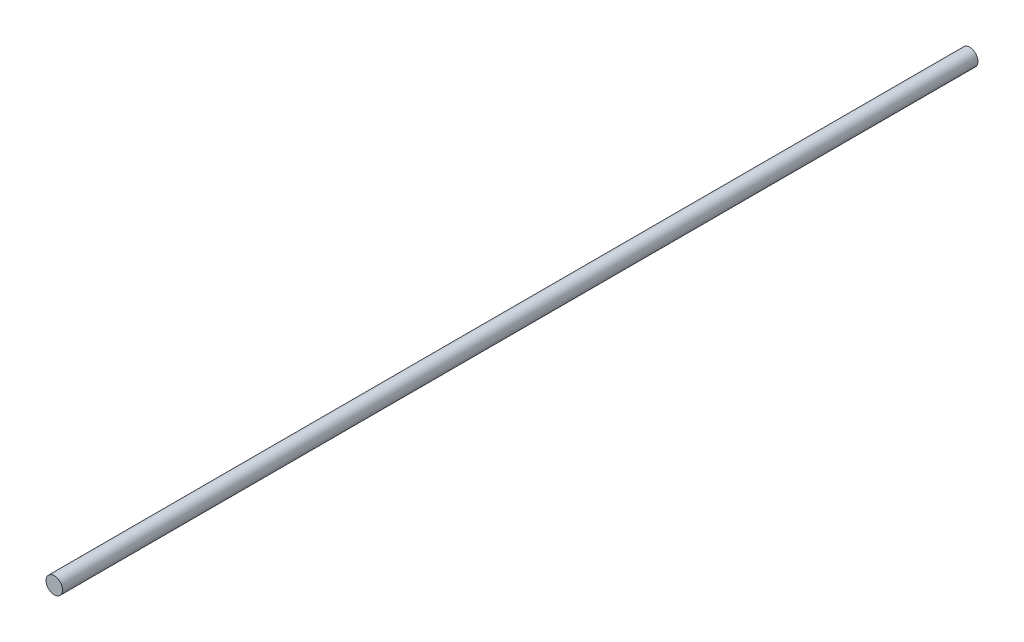
SolidWorks part; units mm, degrees
ref_plane "Front Plane" through (0, 0, 0) normal (0, 0, 1) x (1, 0, 0)
ref_plane "Top Plane" through (0, 0, 0) normal (0, 1, 0) x (1, 0, 0)
ref_plane "Right Plane" through (0, 0, 0) normal (1, 0, 0) x (0, 0, -1)
sketch "Sketch1" plane through (0, 0, 0) normal (0, 0, 1) x (1, 0, 0)
  circle A0 centre (0, 0) radius 7.5
  dimension "D1" = 15
extrude "Boss-Extrude1" add sketch "Sketch1" along normal blind 830
